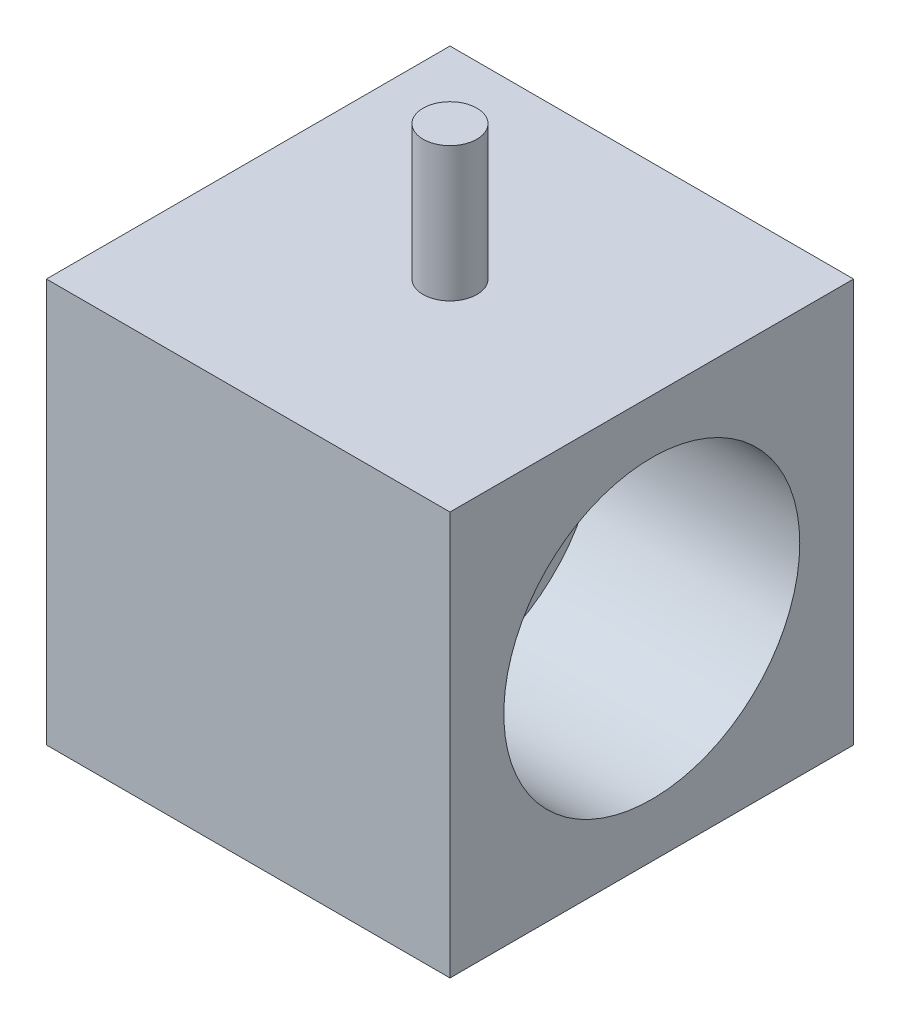
SolidWorks part; units mm, degrees
ref_plane "Front Plane" through (0, 0, 0) normal (0, 0, 1) x (1, 0, 0)
ref_plane "Top Plane" through (0, 0, 0) normal (0, 1, 0) x (1, 0, 0)
ref_plane "Right Plane" through (0, 0, 0) normal (1, 0, 0) x (0, 0, -1)
sketch "Sketch1" plane through (0, 0, 0) normal (0, 1, 0) x (1, 0, 0)
  line L1 (-15, 15) -> (15, 15)
  line L2 (-15, 15) -> (-15, -15)
  line L3 (-15, -15) -> (15, -15)
  line L4 (15, 15) -> (15, -15)
  line L5 (-15, 15) -> (15, -15) construction
  line L6 (-15, -15) -> (15, 15) construction
  point P0 (0, 0)
  dimension "D1" = 30
  dimension "D2" = 30
extrude "Boss-Extrude1" add sketch "Sketch1" along normal blind 30
sketch "Sketch2" plane through (15, 0, 0) normal (1, 0, 0) x (0, 0, -1)
  line L0 (0, 0) -> (0, 30) construction
  line L1 (-15, 0) -> (15, 0) construction
  line L2 (-15, 30) -> (15, 30) construction
  circle A0 centre (0, 15) radius 11
  point P2 (0, 15)
  dimension "D1" = 22
extrude "Cut-Extrude1" cut sketch "Sketch2" against normal blind 15
sketch "Sketch3" plane through (0, 30, 0) normal (0, 1, 0) x (1, 0, 0)
  circle A0 centre (0, 0) radius 2
  dimension "D1" = 4
extrude "Boss-Extrude2" add sketch "Sketch3" along normal blind 10
